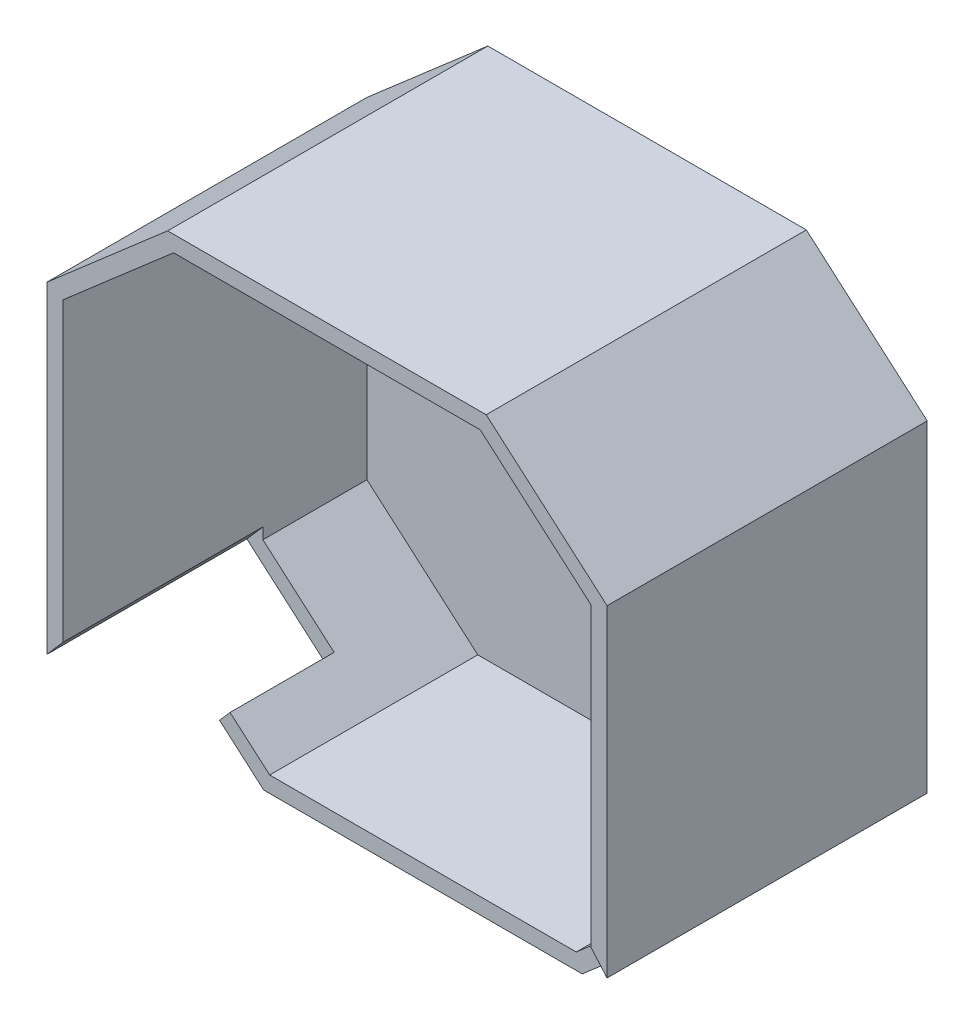
SolidWorks part; units mm, degrees
ref_plane "Front Plane" through (0, 0, 0) normal (0, 0, 1) x (1, 0, 0)
ref_plane "Top Plane" through (0, 0, 0) normal (0, 1, 0) x (1, 0, 0)
ref_plane "Right Plane" through (0, 0, 0) normal (1, 0, 0) x (0, 0, -1)
sketch "Sketch1" plane through (0, 0, 0) normal (0, 0, 1) x (1, 0, 0)
  line L0 (19.15, 31.25) -> (33, 19.2267)
  line L1 (-19.15, -31.25) -> (19.15, -31.25)
  line L2 (-33, -19.2267) -> (-33, 19.2267)
  line L3 (-19.15, 31.25) -> (19.15, 31.25)
  line L4 (33, -19.2267) -> (33, 19.2267)
  line L5 (-26.075, -25.2383) -> (26.075, 25.2383) construction
  line L6 (-26.075, 25.2383) -> (26.075, -25.2383) construction
  line L7 (0, -36.3) -> (0, 36.3) construction
  line L8 (-19.15, 31.25) -> (-33, 19.2267)
  line L9 (38.5, 0) -> (-38.5, 0) construction
  line L10 (19.15, -31.25) -> (33, -19.2267)
  line L11 (-19.15, -31.25) -> (-33, -19.2267)
  line L12 (-19.897, 33.25) -> (-35, 20.139)
  line L13 (-35, -20.139) -> (-35, 20.139)
  line L14 (-19.897, -33.25) -> (-35, -20.139)
  line L15 (-19.897, -33.25) -> (19.897, -33.25)
  line L16 (19.897, -33.25) -> (35, -20.139)
  line L17 (35, -20.139) -> (35, 20.139)
  line L18 (19.897, 33.25) -> (35, 20.139)
  line L19 (-19.897, 33.25) -> (19.897, 33.25)
  point P0 (0, 0)
  point P2 (34, 18.6823)
  point P12 (34, 25.7656)
  point P13 (34, 24.526)
  point P14 (34, 19.7448)
  point P21 (-26.075, 25.2383)
  point P23 (-29.4661, -23.5339)
  point P24 (-26.075, -25.2383)
  point P33 (0, 0)
  dimension "D1" = 66
  dimension "D2" = 20
  dimension "D3" = 38.3
  dimension "D4" = 66.5
  dimension "D5" = 2
extrude "Boss-Extrude1" add sketch "Sketch1" along normal blind 40
sketch "Sketch2" plane through (25.0108, -28.8107, 0) normal (0.6556, -0.7551, 0) x (0.7551, 0.6556, 0)
  line L0 (13.2281, 40) -> (13.2281, 0) construction
  line L1 (13.2281, 15) -> (0.5281, 15)
  line L2 (13.2281, 15) -> (13.2281, 51.2047)
  line L3 (13.2281, 51.2047) -> (0.5281, 51.2047)
  line L4 (0.5281, 15) -> (0.5281, 51.2047)
  line L5 (36.575, 0) -> (-36.575, 0) construction
  dimension "D1" = 15
  dimension "D2" = 12.7
extrude "Cut-Extrude1" cut sketch "Sketch2" against normal up to next
mirror "Mirror1" about plane through (0, 0, 0) normal (1, 0, 0) of "Cut-Extrude1"
sketch "Sketch3" plane through (0, -33.25, 0) normal (0, -1, 0) x (1, 0, 0)
  line L1 (-28.4387, 28) -> (28.0566, 28)
  line L2 (-28.4387, 28) -> (-28.4387, 46.4125)
  line L3 (-28.4387, 46.4125) -> (28.0566, 46.4125)
  line L4 (28.0566, 28) -> (28.0566, 46.4125)
  line L5 (36.575, 0) -> (-36.575, 0) construction
  point P4 (0, 0)
  point P5 (0, 0)
  point P8 (0, 0)
  point P9 (0, 0)
  dimension "D1" = 28
extrude "Cut-Extrude2" cut sketch "Sketch3" against normal up to next
sketch "Sketch4" plane through (0, 0, 0) normal (0, 0, 1) x (1, 0, 0)
  line L0 (19.15, 31.25) -> (33, 19.2267)
  line L1 (33, 19.2267) -> (33, -19.2267)
  line L2 (33, -19.2267) -> (19.15, -31.25)
  line L3 (19.15, -31.25) -> (-19.15, -31.25)
  line L4 (-19.15, -31.25) -> (-33, -19.2267)
  line L5 (-33, -19.2267) -> (-33, 19.2267)
  line L6 (-33, 19.2267) -> (-19.15, 31.25)
  line L7 (-19.15, 31.25) -> (19.15, 31.25)
extrude "Boss-Extrude3" add sketch "Sketch4" along normal blind 2
